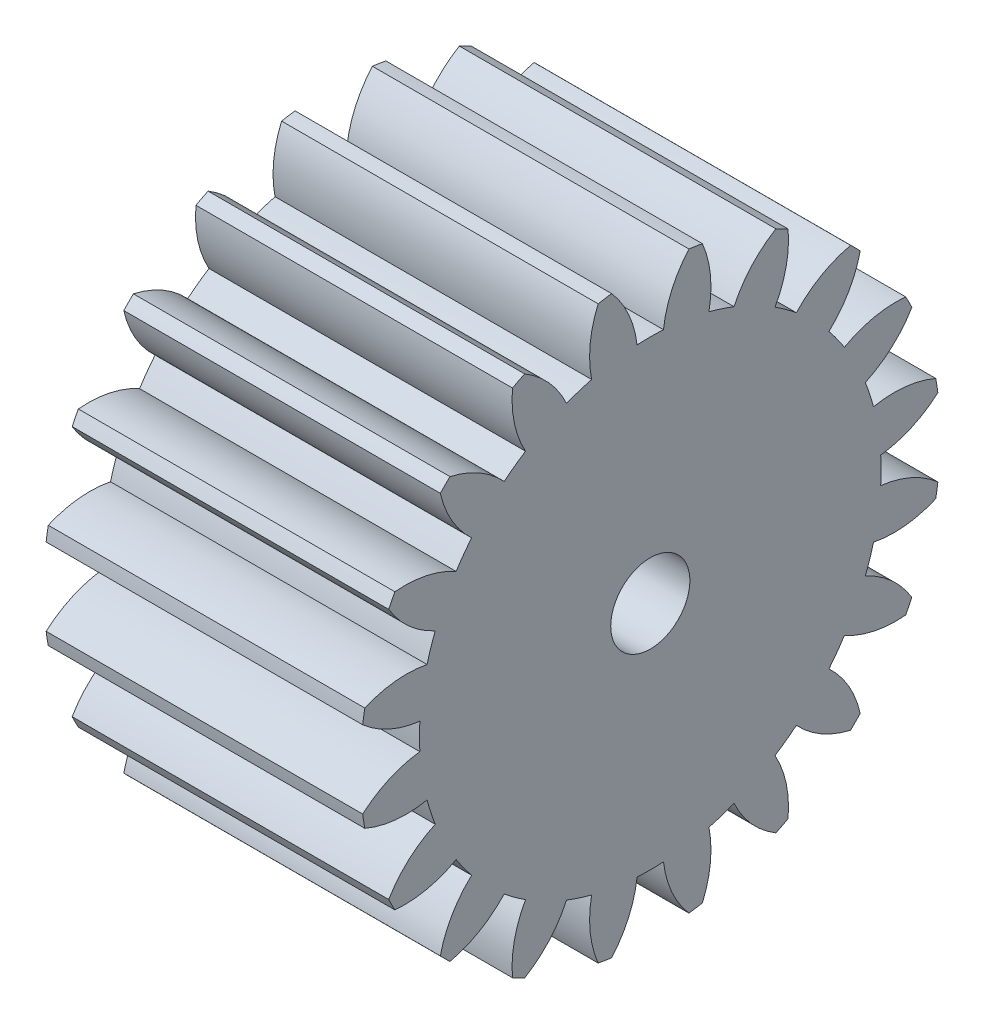
SolidWorks part; units mm, degrees
ref_plane "Plane1" through (0, 0, 0) normal (0, 0, 1) x (1, 0, 0)
ref_plane "Plane2" through (0, 0, 0) normal (0, 1, 0) x (1, 0, 0)
ref_plane "Plane3" through (0, 0, 0) normal (1, 0, 0) x (0, 0, -1)
sketch "HoldingSke" plane through (0, 0, 0) normal (0, 1, 0) x (1, 0, 0)
  line L0 (0, 0) -> (0.9397, -0.342)
  line L1 (-15, 0) -> (100, 0) construction
  line L2 (0, 0) -> (-2.1039, 2.3779)
  line L3 (0, 0) -> (-11.863, 4.5341)
  line L4 (0, 0) -> (8.1152, 2.9537)
  line L5 (0, 0) -> (-46.8476, -17.4728)
  line L6 (0, 0) -> (-9.9476, -6.7116)
  line L7 (-2.1039, 2.3779) -> (8.6586, 51.2059)
  line L8 (-76.2, 54.61) -> (-75.7, 54.61)
  line L9 (-71.009, 38.7566) -> (-53.1078, 45.2721)
  line L10 (-76.2, 71.12) -> (104.1128, 71.12)
  line L11 (0, 0) -> (-12, 0)
  line L12 (-76.2, 101.6) -> (-76.162, 101.6)
  line L13 (24.9733, 27.94) -> (52.9518, 28.4284)
  line L14 (24.9733, 27.94) -> (24.9743, 27.94)
  line L15 (24.9733, 27.94) -> (100.4006, 29.5858)
  line L16 (-63.627, -1) -> (-12.827, -1)
  circle A0 centre (0, 0) radius 1.5
  circle A1 centre (0, 0) radius 8.749
  circle A2 centre (0, 0) radius 37.5
  circle A3 centre (0, 0) radius 1.5
  dimension "MHD" = 17.498
  dimension "Hub_dia" = 75
  dimension "Bore" = 3
  dimension "MBD" = 3
  dimension "Num_teeth" = 20
  dimension "Pitch" = 1
  dimension "Overall_len" = 50
  dimension "Show_teeth" = 20
  dimension "Thickness" = 12
  dimension "OAL" = 50.0001
  dimension "T_dim" = 0.5
  dimension "Ap" = 20
  dimension "H" = 19.05
  dimension "Pitch_radius" = 180.3128
  dimension "Width" = 12
  dimension "Backlash" = 0.038
  dimension "Addendum_fac" = 1
  dimension "Dedendum_fac" = 1.25
  dimension "Clearance_fac" = 0.25
  dimension "Dedendum_add" = 0.001
  dimension "Module" = 1
sketch "BasProSke" plane through (0, 0, 0) normal (0, 1, 0) x (1, 0, 0)
  line L0 (-10, 0) -> (60, 0) construction
  line L1 (0, 0) -> (0, 11)
  line L2 (0, 0) -> (12, 0)
  line L3 (12, 0) -> (12, 11)
  line L4 (12, 11) -> (0, 11)
  dimension "Thickness" = 12
  dimension "Diameter" = 22
revolve "Base-Revolve" add sketch "BasProSke" angle 360 about L0
sketch "TooCutSke" plane through (0, 0, 0) normal (1, 0, 0) x (0, 0, -1)
  line L1 (0, 0) -> (0, 107) construction
  line L2 (0, 0) -> (-0.8511, 9.9637) construction
  line L3 (0, 0) -> (-3.1206, 19.7028) construction
  line L4 (-0.8511, 9.9637) -> (-1.5603, 9.8514) construction
  arc A0 (0.4999, 8.7347) -> (-0.4999, 8.7347) centre (0, 0) ccw
  arc A1 (1.4852, 10.9249) -> (-1.4852, 10.9249) centre (0, 0) ccw
  circle A2 centre (0, 0) radius 10 construction
  circle A3 centre (0, 0) radius 9.3969 construction
  arc A4 (-0.4999, 8.7347) -> (-1.4852, 10.9249) centre (-4.4722, 8.2645) ccw
  arc A5 (1.4852, 10.9249) -> (0.4999, 8.7347) centre (4.4722, 8.2645) ccw
  dimension "Root_dia" = 17.498
  dimension "Overcut_dia" = 22.0508
  dimension "Pitch_dia" = 20
  dimension "Base_dia" = 18.7939
  dimension "Flank_rad" = 4
  dimension "Half_ang" = 9
  dimension "Half_CT" = 0.7181
extrude "ToothCut" cut sketch "TooCutSke" along normal through all
fillet "Breaks" [suppressed] radius 0.02
fillet "RootFillets" [suppressed] radius 0.251
pattern_circular "TeethCuts" count 20 every 18 about axis through (-10, 0, 0) along (1, 0, 0) of "ToothCut", "RootFillets", "Breaks"
sketch "HubNeaOneSke" plane through (0, 0, 0) normal (-1, 0, 0) x (0, 0, 1)
  circle A0 centre (0, 0) radius 8.749
  dimension "Diameter" = 17.498
extrude "HubNearOne" [suppressed] add sketch "HubNeaOneSke" along normal blind 38.0001
sketch "HubNeaBotSke" plane through (0, 0, 0) normal (-1, 0, 0) x (0, 0, 1)
  circle A0 centre (0, 0) radius 8.749
  dimension "Diameter" = 17.498
extrude "HubNearBoth" [suppressed] add sketch "HubNeaBotSke" along normal blind 19
ref_plane "FarPln" through (12, 0, 0) normal (1, 0, 0) x (0, 0, -1)
sketch "HubFarSke" plane through (12, 0, 0) normal (1, 0, 0) x (0, 0, -1)
  circle A0 centre (0, 0) radius 8.749
  dimension "Diameter" = 17.498
extrude "HubFar" [suppressed] add sketch "HubFarSke" along normal blind 19
sketch "BorSke" plane through (0, 0, 0) normal (1, 0, 0) x (0, 0, -1)
  circle A0 centre (0, 0) radius 1.5
  dimension "Diameter" = 3
extrude "Bore" cut sketch "BorSke" along normal mid plane 100.0001
sketch "KeySke" plane through (0, 0, 0) normal (1, 0, 0) x (0, 0, -1)
  line L0 (-0.6, 0) -> (-0.6, 2)
  line L1 (-0.6, 2) -> (0.6, 2)
  line L2 (0.6, 2) -> (0.6, 0)
  line L3 (0, 0) -> (0, 34) construction
  line L4 (-0.6, 0) -> (0.6, 0)
  dimension "Offset" = 2
extrude "Keyway" [suppressed] cut sketch "KeySke" along normal mid plane 100.0001
pattern_circular "Keyway2" [suppressed] count 2 every 90 about axis through (-10, 0, 0) along (1, 0, 0)
equation "' \"Module@HoldingSke\" = 6.35"
equation "' \"Num_teeth@HoldingSke\" = 12"
equation "' \"Ap@HoldingSke\" =  20"
equation "' \"Ap@HoldingSke\" = 20"
equation "' \"Width@HoldingSke\" = 0.5 * 25.4"
equation "' \"Hub_dia@HoldingSke\"= 1 * 25.4"
equation "' \"Hub_dia@HoldingSke\" = 1 * 25.4"
equation "' \"Overall_len@HoldingSke\" = 1.0 * 25.4"
equation "' \"Bore@HoldingSke\" = 0.75 * 25.4"
equation "' \"T_dim@HoldingSke\" = 0.1 * 25.4"
equation "' \"Width@KeySke\" = 0.25 * 25.4"
equation "' \"Show_teeth@HoldingSke\" = 13"
equation "' \"Backlash@HoldingSke\" = 0.009 * 25.4"
equation "' \"Addendum_fac@HoldingSke\" = 1.0"
equation "' \"Dedendum_fac@HoldingSke\" = 1.25"
equation "' \"Dedendum_add@HoldingSke\" = 0.00005 * 25.4"
equation "' \"Clearance_fac@HoldingSke\" = 0.25"
equation "\"Pitch@HoldingSke\" = 1 / \"Module@HoldingSke\""
equation "\"Overcut_dia@TooCutSke\" = (\"Num_teeth@HoldingSke\" + 2 * \"Addendum_fac@HoldingSke\") / \"Pitch@HoldingSke\" + 0.002 * 25.4"
equation "\"Pitch_dia@TooCutSke\" = \"Num_teeth@HoldingSke\" / \"Pitch@HoldingSke\""
equation "\"Base_dia@TooCutSke\" = \"Num_teeth@HoldingSke\" / \"Pitch@HoldingSke\" * cos((\"Ap@HoldingSke\"  * 3.14159265 / 180))"
equation "\"Root_dia@TooCutSke\" = (\"Num_teeth@HoldingSke\" + 2) / \"Pitch@HoldingSke\" - 2 * (\"Addendum_fac@HoldingSke\" + \"Dedendum_fac@HoldingSke\") / \"Pitch@HoldingSke\" - \"Dedendum_add@HoldingSke\" * 2"
equation "\"Half_ang@TooCutSke\" = 180 / \"Num_teeth@HoldingSke\""
equation "\"Half_CT@TooCutSke\" = \"Num_teeth@HoldingSke\" / \"Pitch@HoldingSke\" * sin((3.14159265 / 2 / \"Num_teeth@HoldingSke\")) / 2 - 7 * \"Backlash@HoldingSke\" / 4"
equation "\"Flank_rad@TooCutSke\" = \"Num_teeth@HoldingSke\" / \"Pitch@HoldingSke\" / 5"
equation "\"Radius@RootFillets\" = \"Clearance_fac@HoldingSke\" / \"Pitch@HoldingSke\" + \"Dedendum_add@HoldingSke\""
equation "\"Break_rad@Breaks\" = 0.02 / \"Pitch@HoldingSke\""
equation "\"Thickness@HoldingSke\" = \"Width@HoldingSke\""
equation "\"OAL@HoldingSke\" = \"Thickness@HoldingSke\""
equation "\"MHD@HoldingSke\" = (\"Num_teeth@HoldingSke\" + 2) / \"Pitch@HoldingSke\" - 2 * (\"Addendum_fac@HoldingSke\" + \"Dedendum_fac@HoldingSke\")  / \"Pitch@HoldingSke\" - \"Dedendum_add@HoldingSke\" * 2"
equation "\"MBD@HoldingSke\" = (\"Num_teeth@HoldingSke\" + 2) / \"Pitch@HoldingSke\" - 2 * (\"Addendum_fac@HoldingSke\" + \"Dedendum_fac@HoldingSke\")  / \"Pitch@HoldingSke\" - \"Dedendum_add@HoldingSke\" * 2 - 0.002 * 25.4"
equation "\"MHD@HoldingSke\" = ((sgn( \"MHD@HoldingSke\" - \"Hub_dia@HoldingSke\" )-1)*( \"MHD@HoldingSke\" - \"Hub_dia@HoldingSke\" ))/-2+ \"Hub_dia@HoldingSke\""
equation "\"MBD@HoldingSke\" = ((sgn( \"MBD@HoldingSke\" - \"Bore@HoldingSke\" )-1)*( \"MBD@HoldingSke\" - \"Bore@HoldingSke\" ))/-2+ \"Bore@HoldingSke\""
equation "\"OAL@HoldingSke\" = ((sgn( \"OAL@HoldingSke\" - \"Overall_len@HoldingSke\" )+1)*( \"OAL@HoldingSke\" - \"Overall_len@HoldingSke\" ))/2 + \"Overall_len@HoldingSke\" + 0.000002 * 25.4"
equation "\"Num_teeth@TeethCuts\" = int( \"Show_teeth@HoldingSke\" ) + 1"
equation "\"Num_teeth@TeethCuts\" = ((sgn( \"Num_teeth@TeethCuts\" - \"Num_teeth@HoldingSke\" )-1)*( \"Num_teeth@TeethCuts\" - \"Num_teeth@HoldingSke\" ))/-2+ \"Num_teeth@HoldingSke\""
equation "\"Num_teeth@TeethCuts\" = ((sgn( \"Num_teeth@TeethCuts\" - 2.0)+1)*( \"Num_teeth@TeethCuts\" - 2.0))/2 +2.0"
equation "\"Angle@TeethCuts\" = 360.0 / \"Num_teeth@HoldingSke\""
equation "\"Diameter@BasProSke\" = (\"Num_teeth@HoldingSke\" + 2 * \"Addendum_fac@HoldingSke\") / \"Pitch@HoldingSke\""
equation "\"Thickness@BasProSke\"  = \"Thickness@HoldingSke\""
equation "' \"Fillet_rad@BasProSke\" =  \"Thickness@HoldingSke\" * 0.05"
equation "' \"Fillet_rad@BasProSke\" = \"Thickness@HoldingSke\" * 0.05"
equation "\"MHD@HoldingSke\" = ((sgn( \"MHD@HoldingSke\" - \"Root_dia@TooCutSke\" )-1)*( \"MHD@HoldingSke\" - \"Root_dia@TooCutSke\" ))/-2+ \"Root_dia@TooCutSke\""
equation "\"Diameter@HubNeaOneSke\" = \"MHD@HoldingSke\""
equation "\"Length@HubNearOne\" = \"OAL@HoldingSke\" - \"Thickness@BasProSke\""
equation "\"Diameter@HubNeaBotSke\" = \"MHD@HoldingSke\""
equation "\"Length@HubNearBoth\" = ( \"OAL@HoldingSke\" - \"Thickness@BasProSke\" ) / 2.0"
equation "\"Thickness@FarPln\" = \"Thickness@BasProSke\""
equation "\"Diameter@HubFarSke\" = \"MHD@HoldingSke\""
equation "\"Length@HubFar\" = ( \"OAL@HoldingSke\" - \"Thickness@BasProSke\" ) / 2.0"
equation "\"Diameter@BorSke\" = \"MBD@HoldingSke\""
equation "\"D1@Bore\" = \"OAL@HoldingSke\" * 2.0"
equation "\"D1@Keyway\" = \"OAL@HoldingSke\" * 2.0"
equation "\"Offset@KeySke\" = \"T_dim@HoldingSke\" + \"MBD@HoldingSke\" / 2.0"
